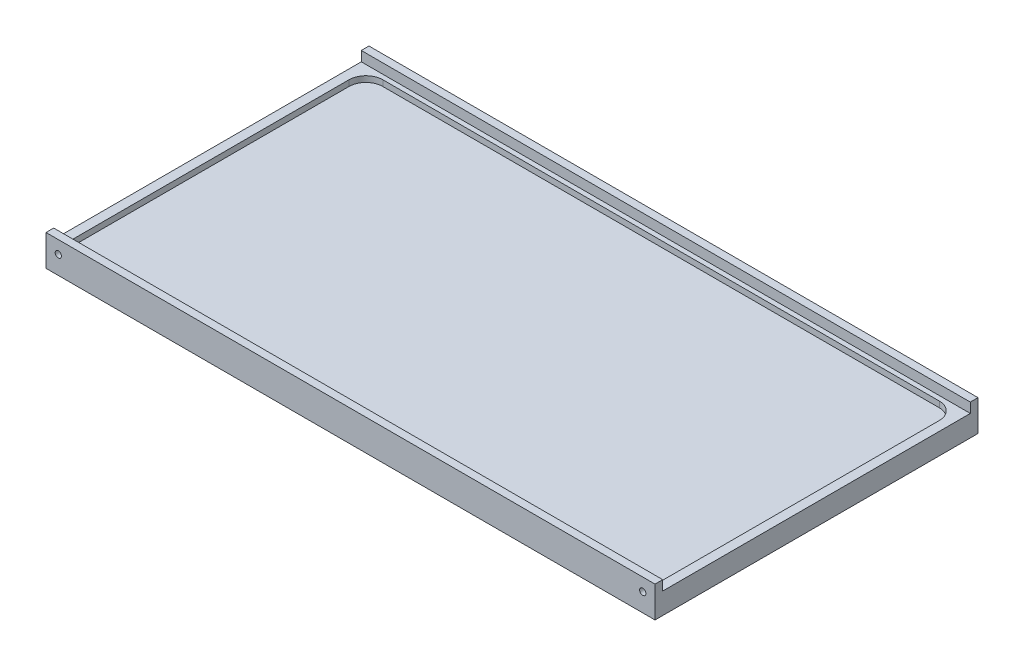
SolidWorks part; units mm, degrees
ref_plane "Front Plane" through (0, 0, 0) normal (0, 0, 1) x (1, 0, 0)
ref_plane "Top Plane" through (0, 0, 0) normal (0, 1, 0) x (1, 0, 0)
ref_plane "Right Plane" through (0, 0, 0) normal (1, 0, 0) x (0, 0, -1)
sketch "Sketch2" plane through (0, 0, 0) normal (0, 0, 1) x (1, 0, 0)
  line L1 (-959.525, 0) -> (959.525, 0)
  line L3 (-1000, -50) -> (1000, -50)
  line L5 (1000, 19.05) -> (959.525, 19.05)
  line L6 (959.525, 19.05) -> (959.525, 0)
  line L7 (1000, 19.05) -> (1000, -50)
  line L9 (-1000, 19.05) -> (-959.525, 19.05)
  line L10 (-959.525, 19.05) -> (-959.525, 0)
  line L11 (-1000, -50) -> (-1000, 19.05)
  dimension "D1" = 2000
  dimension "D2" = 50
  dimension "D3" = 19.05
  dimension "D4" = 40.475
extrude "Boss-Extrude1" add sketch "Sketch2" along normal blind 1009.525
sketch "Sketch3" plane through (0, 0, 0) normal (0, 1, 0) x (1, 0, 0)
  line L0 (-959.525, -40.475) -> (959.525, -40.475)
  line L1 (-959.525, -1009.525) -> (-959.525, 0) construction
  line L2 (959.525, -1009.525) -> (959.525, 0) construction
  line L3 (959.525, -40.475) -> (959.525, 0)
  line L4 (959.525, 0) -> (-959.525, 0)
  line L5 (959.525, 0) -> (-959.525, 0) construction
  line L6 (-959.525, 0) -> (-959.525, -40.475)
  dimension "D1" = 40.475
extrude "Boss-Extrude2" add sketch "Sketch3" along normal up to surface (19.05 mm away) up to face at (-979.7625, 19.05, 504.7625)
fillet "Fillet1" radius 55 2 edges at (-959.525, 9.525, 40.475) (959.525, 9.525, 40.475)
sketch "Sketch4" plane through (0, 0, 0) normal (0, 1, 0) x (1, 0, 0)
  line L0 (-1000, -1009.525) -> (-1000, 0) construction
  line L1 (1000, -1009.525) -> (-1000, -1009.525)
  line L2 (1000, -1009.525) -> (1000, -1050)
  line L3 (1000, -1050) -> (-1000, -1050)
  line L4 (-1000, -1009.525) -> (-1000, -1050)
  point P5 (0, 0)
  dimension "D1" = 40.475
extrude "Boss-Extrude4" add sketch "Sketch4" along normal up to surface (69.05 mm away) from surface at -50 up to face at (0, 19.05, 428.7218) starting at face at (0, -50, 504.7625)
sketch "Sketch6" plane through (0, 0, 0) normal (0, 1, 0) x (1, 0, 0)
  line L0 (1000, 0) -> (1000, -25)
  line L1 (1000, -1050) -> (1000, 0) construction
  line L2 (1000, -25) -> (-1000, -25)
  line L3 (-1000, -1050) -> (-1000, 0) construction
  line L4 (-1000, -25) -> (-1000, 0)
  line L5 (-1000, 0) -> (1000, 0)
  line L6 (1000, -525) -> (-1000, -525) construction
  line L7 (-1000, -1025) -> (-1000, -1050)
  line L8 (-1000, -1050) -> (1000, -1050)
  line L9 (1000, -1050) -> (1000, -1025)
  line L10 (1000, -1025) -> (-1000, -1025)
  dimension "D1" = 1000
extrude "Boss-Extrude6" add sketch "Sketch6" along normal blind 32 from surface at 19.05 starting at face at (0, 19.05, 378.028)
sketch "Sketch5" plane through (0, 0, 0) normal (0, 0, 1) x (1, 0, 0)
  line L0 (-1000, 51.05) -> (1000, 51.05) construction
  line L1 (1000, 19.05) -> (-1000, 19.05) construction
  line L3 (0, 19.05) -> (0, -50) construction
  line L4 (-1000, -50) -> (1000, -50) construction
  circle A3 centre (-950, 9.525) radius 10.16
  circle A5 centre (950, 9.525) radius 10.16
  dimension "D1" = 41.525
  dimension "D2" = 950
  dimension "D3" = 20.32
extrude "Cut-Extrude5" cut sketch "Sketch5" against normal up to surface (25 mm away) from surface at 1050 up to face at (0, 35.05, 1025) starting at face at (0, 0.525, 1050)
sketch "Sketch7" plane through (0, 0, 0) normal (0, 0, 1) x (1, 0, 0)
  line L0 (-1000, 51.05) -> (-990, 51.05)
  line L1 (-1000, 51.05) -> (1000, 51.05) construction
  line L2 (-990, 51.05) -> (-990, -50)
  line L3 (-1000, -50) -> (1000, -50) construction
  line L4 (-990, -50) -> (-1000, -50)
  line L5 (-1000, -50) -> (-1000, 51.05)
  line L6 (0, 0) -> (0, 51.05) construction
  line L7 (990, 51.05) -> (990, -50)
  line L8 (990, -50) -> (1000, -50)
  line L9 (1000, -50) -> (1000, 51.05)
  line L10 (1000, 51.05) -> (990, 51.05)
  dimension "D1" = 10
extrude "Cut-Extrude6" cut sketch "Sketch7" along normal through all
